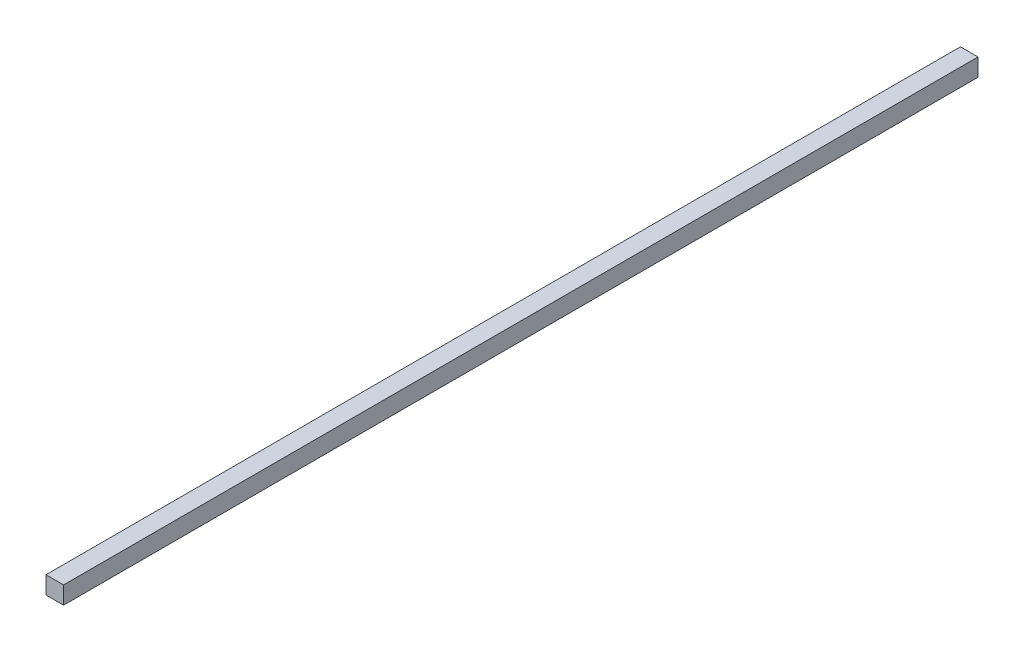
SolidWorks part; units mm, degrees
ref_plane "Front Plane" through (0, 0, 0) normal (0, 0, 1) x (1, 0, 0)
ref_plane "Top Plane" through (0, 0, 0) normal (0, 1, 0) x (1, 0, 0)
ref_plane "Right Plane" through (0, 0, 0) normal (1, 0, 0) x (0, 0, -1)
sketch "Sketch1" plane through (0, 0, 0) normal (0, 0, 1) x (1, 0, 0)
  line L1 (-2.5, -2.5) -> (2.5, -2.5)
  line L2 (-2.5, -2.5) -> (-2.5, 2.5)
  line L3 (-2.5, 2.5) -> (2.5, 2.5)
  line L4 (2.5, -2.5) -> (2.5, 2.5)
  line L5 (-2.5, -2.5) -> (2.5, 2.5) construction
  line L6 (-2.5, 2.5) -> (2.5, -2.5) construction
  point P0 (0, 0)
  dimension "D1" = 5
  dimension "D2" = 5
extrude "Boss-Extrude1" add sketch "Sketch1" along normal blind 260
